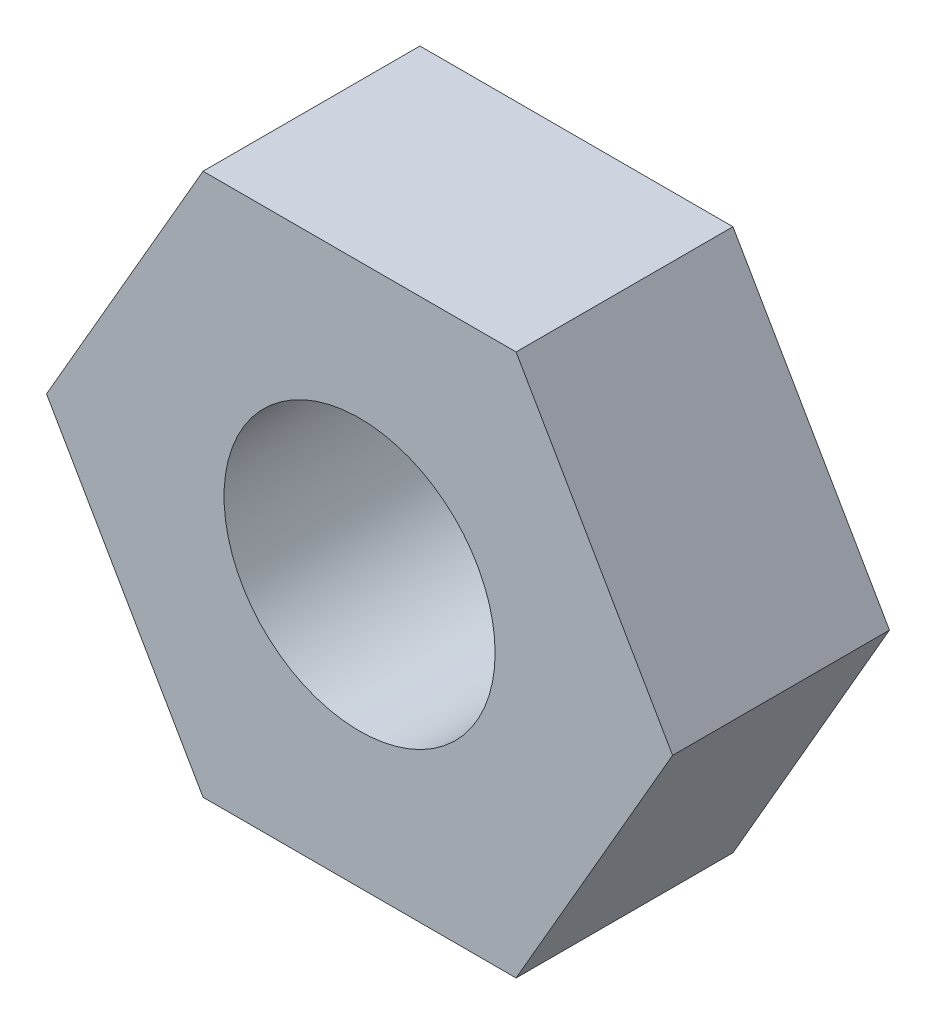
SolidWorks part; units mm, degrees
ref_plane "Front" through (0, 0, 0) normal (0, 0, 1) x (1, 0, 0)
ref_plane "Top" through (0, 0, 0) normal (0, 1, 0) x (1, 0, 0)
ref_plane "Right" through (0, 0, 0) normal (1, 0, 0) x (0, 0, -1)
sketch "Base" plane through (0, 0, 0) normal (0, 0, 1) x (1, 0, 0)
  line L1 (1.1547, 2) -> (-1.1547, 2)
  line L2 (-1.1547, 2) -> (-2.3094, 0)
  line L3 (-2.3094, 0) -> (-1.1547, -2)
  line L4 (-1.1547, -2) -> (1.1547, -2)
  line L5 (1.1547, -2) -> (2.3094, 0)
  line L6 (2.3094, 0) -> (1.1547, 2)
  circle A0 centre (0, 0) radius 2 construction
  circle A1 centre (0, 0) radius 1
  dimension "D2" = 2
  dimension "D1" = 4
extrude "Body" add sketch "Base" along normal blind 1.6
equation "\"screw_diameter\"=2"
equation "\"D2@Base\"=\"screw_diameter\""
equation "\"nut_size\"=4"
equation "\"D1@Base\"=\"nut_size\""
